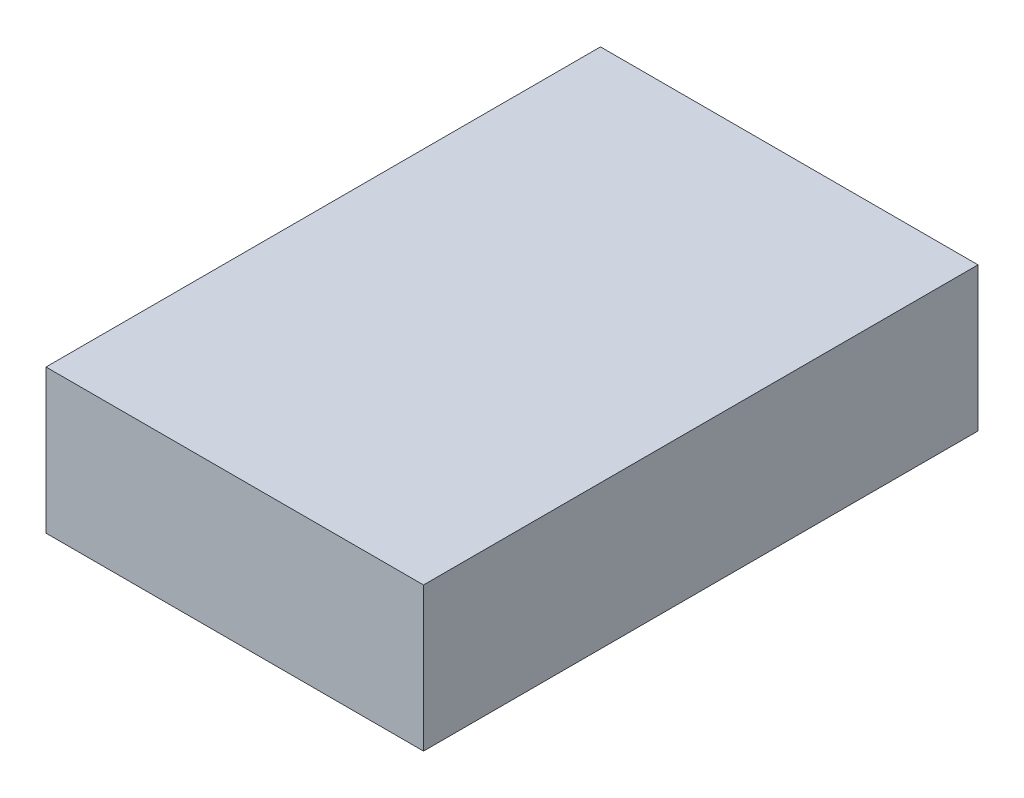
SolidWorks part; units mm, degrees
ref_plane "前视基准面" through (0, 0, 0) normal (0, 0, 1) x (1, 0, 0)
ref_plane "上视基准面" through (0, 0, 0) normal (0, 1, 0) x (1, 0, 0)
ref_plane "右视基准面" through (0, 0, 0) normal (1, 0, 0) x (0, 0, -1)
sketch "草图1" plane through (0, 0, 0) normal (0, 1, 0) x (1, 0, 0)
  line L1 (-16, -23.5) -> (16, -23.5)
  line L2 (-16, -23.5) -> (-16, 23.5)
  line L3 (-16, 23.5) -> (16, 23.5)
  line L4 (16, -23.5) -> (16, 23.5)
  line L5 (-16, -23.5) -> (16, 23.5) construction
  line L6 (-16, 23.5) -> (16, -23.5) construction
  point P0 (0, 0)
  dimension "D1" = 47
  dimension "D2" = 32
extrude "凸台-拉伸1" add sketch "草图1" along normal blind 12.2
